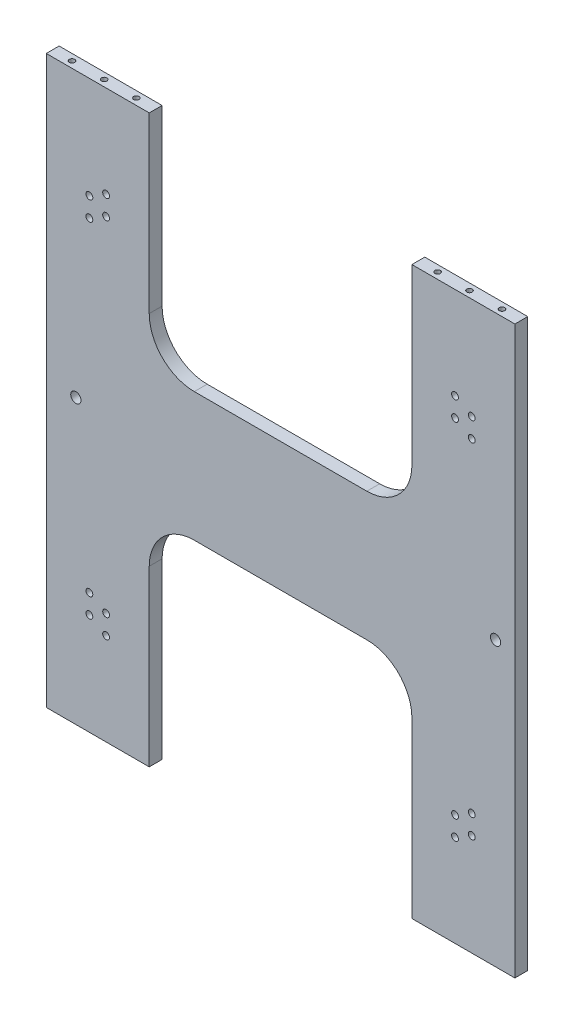
SolidWorks part; units mm, degrees
material "ABS"
ref_plane "Alzado" through (0, 0, 0) normal (0, 0, 1) x (1, 0, 0)
ref_plane "Planta" through (0, 0, 0) normal (0, 1, 0) x (1, 0, 0)
ref_plane "Vista lateral" through (0, 0, 0) normal (1, 0, 0) x (0, 0, -1)
sketch "Croquis1" plane through (0, 0, 0) normal (0, 0, 1) x (1, 0, 0)
  line L0 (0, -445.6503) -> (0, 445.6503) construction
  line L1 (0, 0) -> (589.6913, 0) construction
  line L2 (-67.025, 50) -> (67.025, 50)
  line L3 (102.025, 85) -> (102.025, 220)
  line L4 (102.025, 220) -> (182.025, 220)
  line L5 (182.025, 220) -> (182.025, 60)
  line L6 (-182.025, 220) -> (-182.025, 60)
  line L7 (-102.025, 220) -> (-182.025, 220)
  line L8 (-102.025, 85) -> (-102.025, 220)
  line L9 (-102.025, -85) -> (-102.025, -220)
  line L10 (-102.025, -220) -> (-182.025, -220)
  line L11 (-182.025, -220) -> (-182.025, -60)
  line L12 (182.025, -220) -> (182.025, -60)
  line L13 (102.025, -220) -> (182.025, -220)
  line L14 (102.025, -85) -> (102.025, -220)
  line L15 (-67.025, -50) -> (67.025, -50)
  line L16 (-182.025, 60) -> (-182.025, -60)
  line L17 (182.025, 60) -> (182.025, -60)
  arc A0 (67.025, 50) -> (102.025, 85) centre (67.025, 85) ccw
  arc A5 (-67.025, 50) -> (-102.025, 85) centre (-67.025, 85) cw
  arc A6 (-67.025, -50) -> (-102.025, -85) centre (-67.025, -85) ccw
  arc A9 (67.025, -50) -> (102.025, -85) centre (67.025, -85) cw
  point P10 (0, 0)
  point P39 (0, 50)
  point P54 (0, -50)
  dimension "D6" = 35
  dimension "D1" = 80
  dimension "D2" = 440
  dimension "D3" = 364.05
  dimension "D7" = 100
extrude "Saliente-Extruir1" add sketch "Croquis1" along normal blind 10
sketch "Croquis2" plane through (0, 220, 0) normal (0, 1, 0) x (1, 0, 0)
  line L0 (-102.025, -10) -> (-182.025, -10) construction
  line L1 (0, 0) -> (0, -10) construction
  line L2 (67.025, -10) -> (-67.025, -10) construction
  line L3 (-182.025, -10) -> (-182.025, 0) construction
  point P6 (-142.025, -5)
  point P7 (167.025, -5)
  point P8 (-117.025, -5)
  point P9 (-167.025, -5)
  point P11 (117.025, -5)
  point P15 (142.025, -5)
  dimension "D1" = 15
  dimension "D2" = 5
  dimension "D3" = 25
  dimension "D4" = 25
  dimension "D5" = 25
  dimension "D6" = 25
  dimension "D7" = 117.025
hole_wizard "Perforador para roscar para macho de roscar para M5x0.81" positions "Croquis3D2" profile "Croquis3" hole size "M5x0.8" standard "Ansi Metric"
sketch3d "Croquis3D2"
  point P0 (-167.025, 220, 5)
  point P3 (-117.025, 220, 5)
  point P6 (-271.0773, 0, -42.2427)
  point P8 (-142.025, 220, 5)
sketch "Croquis3" plane through (-167.025, 220, 5) normal (1, 0, 0) x (0, 0, 1)
  line L0 (0, 0) -> (0, 76.2618)
  line L1 (0, 76.2618) -> (2.1, 75)
  line L2 (2.1, 75) -> (2.1, 0)
  line L5 (2.1, 0) -> (0, 0)
  line L10 (0, 76.2618) -> (-2.1, 75) construction
  line L11 (0, -6.35) -> (0, 107.95) construction
  dimension "Diámetro de taladro" = 4.2
  dimension "Profundidad de taladro" = 75
  dimension "Ángulo de perforador" = 118
hole_wizard "Perforador para roscar para macho de roscar para M5x0.82" positions "Croquis3D4" profile "Croquis5" hole size "M5x0.8" standard "Ansi Metric"
sketch3d "Croquis3D4"
  point P0 (117.025, 220, 5)
  point P3 (167.025, 220, 5)
  point P6 (141.9, 220, 5.1379)
sketch "Croquis5" plane through (117.025, 220, 5) normal (1, 0, 0) x (0, 0, 1)
  line L0 (0, 0) -> (0, 76.2618)
  line L1 (0, 76.2618) -> (2.1, 75)
  line L2 (2.1, 75) -> (2.1, 0)
  line L5 (2.1, 0) -> (0, 0)
  line L10 (0, 76.2618) -> (-2.1, 75) construction
  line L11 (0, -6.35) -> (0, 107.95) construction
  dimension "Diámetro de taladro" = 4.2
  dimension "Profundidad de taladro" = 75
  dimension "Ángulo de perforador" = 118
mirror "Simetría1" about plane through (0, 0, 0) normal (0, 1, 0) of "Perforador para roscar para macho de roscar para M5x0.82", "Perforador para roscar para macho de roscar para M5x0.81"
sketch "Croquis6" plane through (0, 0, 0) normal (0, 0, -1) x (-1, 0, 0)
  line L0 (-219.6532, -133.5) -> (279.6893, -133.5) construction
  line L3 (-142.025, -220) -> (-142.025, 252.46) construction
  line L4 (-102.025, -220) -> (-182.025, -220) construction
  line L5 (-148.5202, -141) -> (-148.5202, -126) construction
  line L6 (-148.5202, -126) -> (-135.5298, -133.5) construction
  line L7 (-135.5298, -133.5) -> (-148.5202, -141) construction
  line L8 (-148.5202, -133.5) -> (-135.5298, -133.5) construction
  line L9 (-142.025, -137.25) -> (-148.5202, -126) construction
  line L10 (-148.5202, -141) -> (-135.5298, -148.5) construction
  line L11 (-135.5298, -148.5) -> (-135.5298, -133.5) construction
  line L12 (-142.025, -144.75) -> (-135.5298, -133.5) construction
  line L13 (-148.5202, -126) -> (-135.5298, -126) construction
  line L14 (-142.025, -126) -> (-142.025, -159.2966) construction
  point P16 (-142.025, -126)
  point P17 (-144.1901, -133.5)
  dimension "D1" = 15
  dimension "D2" = 86.5
  dimension "D3" = 79
hole_wizard "Refrentado para tornillo tapón con cabeza plana de clavija de M51" positions "Croquis3D5" profile "Croquis7" countersink size "M5" standard "Ansi Metric" end condition up to next
sketch3d "Croquis3D5"
  point P0 (148.5202, -141, 0)
  point P3 (135.5298, -133.5, 0)
  point P6 (135.5298, -148.5, 0)
  point P9 (148.5202, -126, 0)
sketch "Croquis7" plane through (148.5202, -141, 0) normal (1, 0, 0) x (0, 1, 0)
  line L0 (0, 0) -> (0, 10.001)
  line L1 (0, 10.001) -> (2.65, 10.001)
  line L2 (2.65, 10.001) -> (2.65, 2.95)
  line L3 (2.65, 2.95) -> (5.6, 0)
  line L5 (5.6, 0) -> (0, 0)
  line L6 (-2.65, 2.95) -> (-5.6, 0) construction
  line L11 (0, -6.35) -> (0, 107.95) construction
  dimension "Diámetro de taladro hasta el siguiente" = 5.3
  dimension "Profundidad de taladro hasta el siguiente" = 10.001
  dimension "Diámetro de avellanado cercano" = 11.2
  dimension "Ángulo de avellanado cercano" = 90
mirror "Simetría2" about plane through (0, 0, 0) normal (0, 1, 0) of "Refrentado para tornillo tapón con cabeza plana de clavija de M51"
mirror "Simetría3" about plane through (0, 0, 0) normal (1, 0, 0) of "Simetría2", "Refrentado para tornillo tapón con cabeza plana de clavija de M51"
sketch "Croquis8" plane through (0, 0, 10) normal (0, 0, 1) x (1, 0, 0)
  line L0 (-182.025, 220) -> (-182.025, -220) construction
  line L1 (182.025, -220) -> (182.025, 220) construction
  circle A0 centre (167.025, 0) radius 4
  circle A1 centre (-159.025, 0) radius 4
  dimension "D1" = 8
  dimension "D2" = 23
  dimension "D3" = 15
extrude "Cortar-Extruir1" cut sketch "Croquis8" against normal through all both and the other way through all contours A1 | A0
